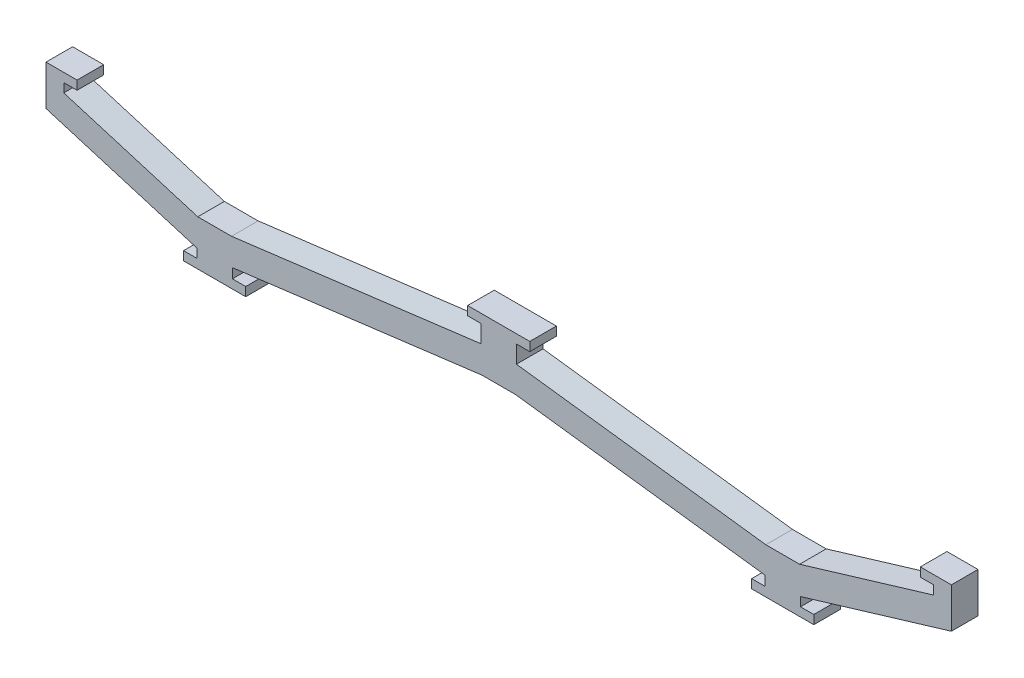
SolidWorks part; units mm, degrees
ref_plane "Plan de face" through (0, 0, 0) normal (0, 0, 1) x (1, 0, 0)
ref_plane "Plan de dessus" through (0, 0, 0) normal (0, 1, 0) x (1, 0, 0)
ref_plane "Plan de droite" through (0, 0, 0) normal (1, 0, 0) x (0, 0, -1)
sketch "Esquisse1" plane through (0, 0, 0) normal (0, 0, 1) x (1, 0, 0)
  line L1 (87.5, 11.7711) -> (87.5, -108.2113) construction
  line L5 (-7.5, 10) -> (10, 10)
  line L8 (78, -22.7068) -> (97, -22.7068)
  line L13 (10, 5) -> (10, 10)
  line L14 (2.5, 5) -> (10, 5)
  line L15 (2.5, 0) -> (2.5, 5)
  line L58 (-7.5, 10) -> (-7.5, -12.6562)
  line L60 (97, -22.7068) -> (237.5, -4.8808)
  line L69 (237.5, -4.8808) -> (237.5, 5)
  line L91 (237.5, 5) -> (230, 5)
  line L92 (230, 5) -> (230, 10)
  line L93 (230, 10) -> (265, 10)
  line L94 (97.5, -37.7636) -> (238, -19.9376)
  line L95 (238, -19.9376) -> (257, -19.9376)
  line L96 (247.5, 49.3646) -> (247.5, -48.9236) construction
  line L97 (397.5, -37.7636) -> (257, -19.9376)
  line L98 (265, 5) -> (265, 10)
  line L99 (257.5, 5) -> (265, 5)
  line L100 (502.5, -12.6562) -> (417.5, -38.2201)
  line L101 (257.5, -4.8808) -> (257.5, 5)
  line L103 (398, -22.7068) -> (257.5, -4.8808)
  line L105 (502.5, 10) -> (502.5, -12.6562)
  line L108 (492.5, 0) -> (417, -22.7068)
  line L109 (492.5, 0) -> (492.5, 5)
  line L110 (492.5, 5) -> (485, 5)
  line L111 (485, 5) -> (485, 10)
  line L115 (417, -22.7068) -> (398, -22.7068)
  line L116 (502.5, 10) -> (485, 10)
  line L118 (78, -22.7068) -> (2.5, 0)
  line L119 (-7.5, -12.6562) -> (77.5, -38.2201)
  line L120 (77.5, -38.2201) -> (77.5, -43.2201)
  line L121 (77.5, -43.2201) -> (70, -43.2201)
  line L122 (70, -43.2201) -> (70, -48.2201)
  line L123 (70, -48.2201) -> (105, -48.2201)
  line L124 (105, -43.2201) -> (105, -48.2201)
  line L125 (97.5, -43.2201) -> (105, -43.2201)
  line L126 (97.5, -43.2201) -> (97.5, -37.7636)
  line L127 (397.5, -43.2201) -> (397.5, -37.7636)
  line L128 (397.5, -43.2201) -> (390, -43.2201)
  line L129 (390, -43.2201) -> (390, -48.2201)
  line L130 (425, -48.2201) -> (390, -48.2201)
  line L131 (425, -43.2201) -> (425, -48.2201)
  line L132 (417.5, -43.2201) -> (425, -43.2201)
  line L133 (417.5, -38.2201) -> (417.5, -43.2201)
  point P15 (87.5, -48.2201)
  point P27 (87.5, -22.7068)
  point P29 (247.5, -19.9376)
  point P33 (247.5, 10)
  point P40 (127.5, -43.2331)
  point P41 (138.1871, -43.2331)
  point P51 (407.5, -48.2201)
  point P54 (407.5, -22.7068)
  dimension "D2" = 17.5
  dimension "D3" = 7.5
  dimension "D4" = 5
  dimension "D5" = 15
  dimension "D6" = 5
  dimension "D7" = 5
  dimension "D8" = 19
  dimension "D9" = 5
  dimension "D10" = 10
  dimension "D11" = 17.5
  dimension "D12" = 95
  dimension "D13" = 17.5
  dimension "D14" = 10
  dimension "D15" = 7.231
  dimension "D16" = 5
  dimension "D17" = 0.5
  dimension "D18" = 15
  dimension "D20" = 160
extrude "Boss.-Extru.1" add sketch "Esquisse1" along normal blind 15
